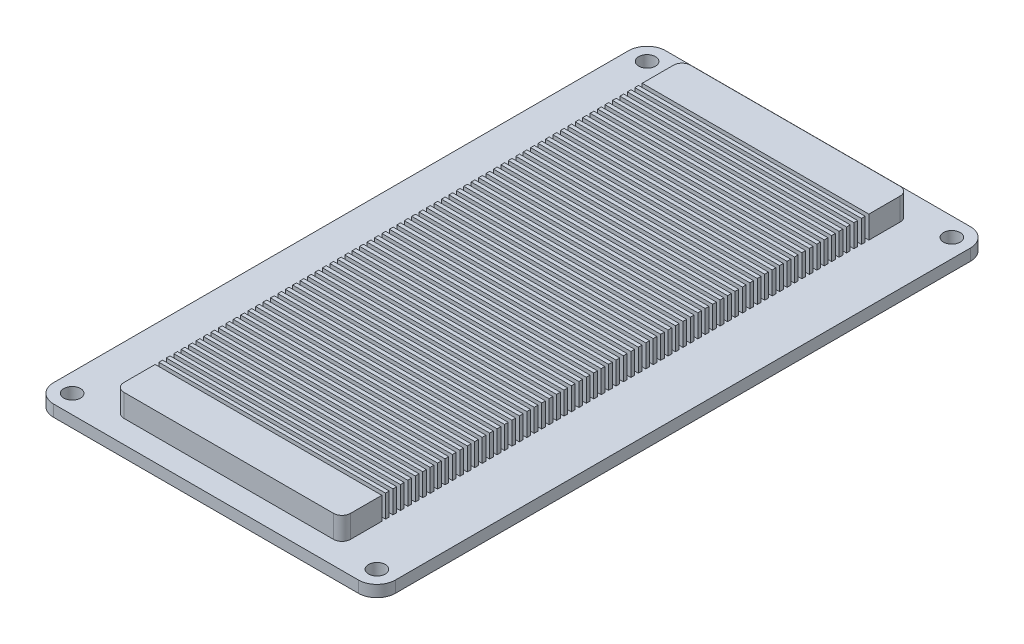
SolidWorks part; units mm, degrees
ref_plane "Front Plane" through (0, 0, 0) normal (0, 0, 1) x (1, 0, 0)
ref_plane "Top Plane" through (0, 0, 0) normal (0, 1, 0) x (1, 0, 0)
ref_plane "Right Plane" through (0, 0, 0) normal (1, 0, 0) x (0, 0, -1)
sketch "Sketch1" plane through (0, 0, 0) normal (0, 1, 0) x (1, 0, 0)
  line L1 (-45.974, -82.3087) -> (45.974, -82.3087)
  line L2 (-45.974, -82.3087) -> (-45.974, 82.3087)
  line L3 (-45.974, 82.3087) -> (45.974, 82.3087)
  line L4 (45.974, -82.3087) -> (45.974, 82.3087)
  line L5 (-45.974, -82.3087) -> (45.974, 82.3087) construction
  line L6 (-45.974, 82.3087) -> (45.974, -82.3087) construction
  point P0 (0, 0)
  dimension "D1" = 164.6174
  dimension "D2" = 91.948
extrude "Boss-Extrude1" add sketch "Sketch1" along normal blind 3.1115
sketch "Sketch5" plane through (0, 3.1115, 0) normal (0, 1, 0) x (1, 0, 0)
  line L0 (0, 0) -> (0, 92.892) construction
  line L1 (0, 0) -> (88.2474, 0) construction
  line L2 (0, 82.3087) -> (-45.974, 82.3087)
  line L3 (45.974, 82.3087) -> (-45.974, 82.3087) construction
  line L4 (45.974, -82.3087) -> (45.974, 82.3087) construction
  line L5 (45.974, 77.3176) -> (45.974, 82.3087)
  line L8 (45.974, -82.3087) -> (45.974, 82.3087)
  line L9 (45.974, 82.3087) -> (-45.974, 82.3087)
  line L10 (-45.974, 82.3087) -> (-45.974, -82.3087)
  line L11 (-45.974, -82.3087) -> (45.974, -82.3087)
  line L12 (45.974, -82.3087) -> (45.974, 0)
  line L13 (45.974, 82.3087) -> (40.9829, 82.3087)
  line L14 (-45.974, 82.3087) -> (-45.974, -82.3087)
  line L15 (-45.974, -82.3087) -> (45.974, -82.3087)
  circle A0 centre (40.9829, 77.3176) radius 2.2479
  arc A1 (45.974, 77.3176) -> (40.9829, 82.3087) centre (40.9829, 77.3176) ccw
  point P6 (40.9829, 79.5655)
  point P7 (43.2308, 77.3176)
  dimension "D1" = 4.4958
  dimension "D2" = 2.7432
  dimension "D3" = 2.7432
  dimension "D4" = 0
extrude "Cut-Extrude2" cut sketch "Sketch5" against normal through all contours A0 | L5 L13 A1
mirror "Mirror1" about plane through (0, 0, 0) normal (1, 0, 0) of "Cut-Extrude2" second plane through (0, 0, 0) second plane normal (0, 0, 1)
sketch "Sketch6" plane through (0, 0, 0) normal (0, -1, 0) x (1, 0, 0)
  line L0 (0, 0) -> (0, 47.498) construction
  line L1 (-12.7, -15.875) -> (12.7, -15.875)
  line L2 (-12.7, -15.875) -> (-12.7, 15.875)
  line L3 (-12.7, 15.875) -> (12.7, 15.875)
  line L4 (12.7, -15.875) -> (12.7, 15.875)
  line L5 (-12.7, -15.875) -> (12.7, 15.875) construction
  line L6 (-12.7, 15.875) -> (12.7, -15.875) construction
  line L7 (0, 0) -> (29.0288, 0) construction
  line L8 (-12.7, 63.373) -> (12.7, 63.373)
  line L9 (-12.7, 63.373) -> (-12.7, 31.623)
  line L10 (-12.7, 31.623) -> (12.7, 31.623)
  line L11 (12.7, 63.373) -> (12.7, 31.623)
  line L12 (-12.7, 63.373) -> (12.7, 31.623) construction
  line L13 (-12.7, 31.623) -> (12.7, 63.373) construction
  line L14 (-12.7, -31.623) -> (12.7, -63.373) construction
  line L15 (-12.7, -63.373) -> (12.7, -31.623) construction
  line L16 (12.7, -63.373) -> (12.7, -31.623)
  line L17 (-12.7, -31.623) -> (12.7, -31.623)
  line L18 (-12.7, -63.373) -> (-12.7, -31.623)
  line L19 (-12.7, -63.373) -> (12.7, -63.373)
  point P0 (0, 0)
  dimension "D1" = 31.75
  dimension "D2" = 25.4
  dimension "D3" = 47.498
  dimension "D4" = 31.75
  dimension "D5" = 25.4
split line "Split Line1"
sketch "Sketch7" plane through (0, 3.1115, 0) normal (0, 1, 0) x (1, 0, 0)
  line L0 (-14.605, -63.5) -> (-20.955, -63.5) construction
  line L1 (-24.13, -64.5) -> (-30.48, -64.5) construction
  line L2 (-14.605, -63.5) -> (-20.955, -63.5) construction
  line L3 (-24.13, -64.5) -> (-30.48, -64.5) construction
  line L4 (30.48, 73.914) -> (30.48, -73.914) construction
  line L5 (-30.48, -73.914) -> (-30.48, 73.914) construction
  line L6 (30.48, 73.914) -> (30.48, -73.914) construction
  line L7 (-30.48, -73.914) -> (-30.48, 73.914) construction
  line L9 (-30.48, -64.5) -> (30.48, -64.5)
  line L10 (-30.48, -64.5) -> (-30.48, -63.5)
  line L11 (-30.48, -63.5) -> (30.48, -63.5)
  line L12 (30.48, -64.5) -> (30.48, -63.5)
extrude "Boss-Extrude2" add sketch "Sketch7" along normal up to surface (6.0706 mm away)
pattern_linear "LPattern1" count 66 spacing 2 along (0, 0, -1) count 2 spacing 2 along (0, 0, 1) of "Boss-Extrude2"
sketch "Sketch8" plane through (0, 3.1115, 0) normal (0, 1, 0) x (1, 0, 0)
  line L0 (28.194, -76.2) -> (-28.194, -76.2) construction
  line L1 (30.48, 73.914) -> (30.48, -73.914) construction
  line L3 (-28.194, 76.2) -> (28.194, 76.2) construction
  line L4 (28.194, -76.2) -> (-28.194, -76.2)
  line L5 (30.48, 73.914) -> (30.48, 66.5)
  line L6 (-30.48, -73.914) -> (-30.48, -66.5)
  line L7 (-28.194, 76.2) -> (28.194, 76.2)
  line L8 (30.48, 66.5) -> (-30.48, 66.5) construction
  line L9 (-30.48, -66.5) -> (30.48, -66.5) construction
  line L10 (30.48, 66.5) -> (-30.48, 66.5)
  line L11 (-30.48, -66.5) -> (30.48, -66.5)
  line L12 (-30.48, 66.5) -> (-30.48, 73.914)
  line L13 (30.48, -66.5) -> (30.48, -73.914)
  arc A0 (-30.48, -73.914) -> (-28.194, -76.2) centre (-28.194, -73.914) ccw construction
  arc A1 (28.194, -76.2) -> (30.48, -73.914) centre (28.194, -73.914) ccw construction
  arc A2 (30.48, 73.914) -> (28.194, 76.2) centre (28.194, 73.914) ccw construction
  arc A3 (-28.194, 76.2) -> (-30.48, 73.914) centre (-28.194, 73.914) ccw construction
  arc A4 (-30.48, -73.914) -> (-28.194, -76.2) centre (-28.194, -73.914) ccw
  arc A5 (28.194, -76.2) -> (30.48, -73.914) centre (28.194, -73.914) ccw
  arc A6 (30.48, 73.914) -> (28.194, 76.2) centre (28.194, 73.914) ccw
  arc A7 (-28.194, 76.2) -> (-30.48, 73.914) centre (-28.194, 73.914) ccw
extrude "Boss-Extrude3" add sketch "Sketch8" along normal up to surface (6.0706 mm away) contours A5 L13 L11 L6 A4 L4 | L5 L10 L12 A7 L7 A6
